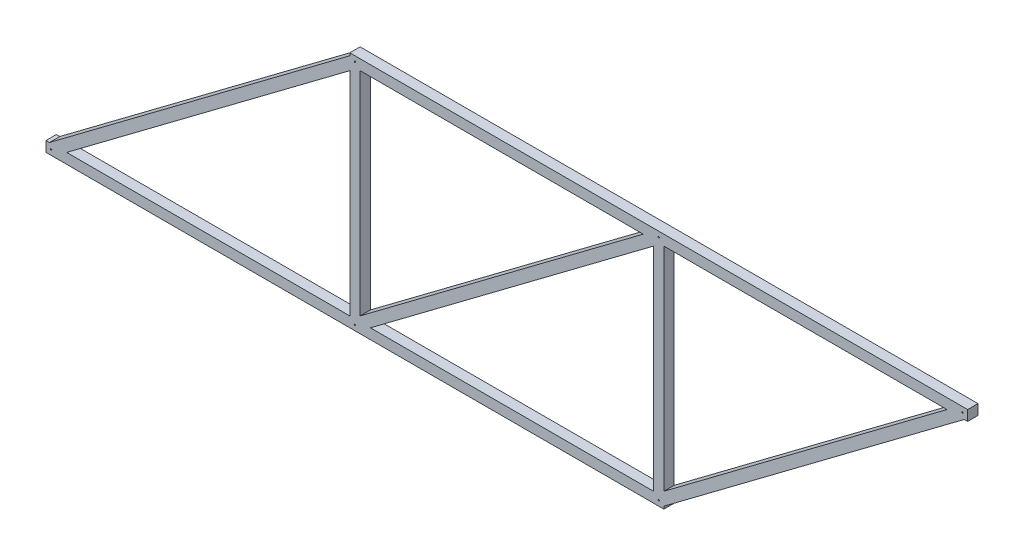
SolidWorks part; units mm, degrees
material "ASTM A36 Steel"
ref_plane "Front Plane" through (0, 0, 0) normal (0, 0, 1) x (1, 0, 0)
ref_plane "Top Plane" through (0, 0, 0) normal (0, 1, 0) x (1, 0, 0)
ref_plane "Right Plane" through (0, 0, 0) normal (1, 0, 0) x (0, 0, -1)
sketch "Sketch1" plane through (0, 0, 0) normal (0, 0, 1) x (1, 0, 0)
  line L0 (0, 321.0136) -> (0, -315.4549) construction
  line L1 (400, 0) -> (-400, 0)
  line L5 (0, 321.0136) -> (0, 1472.7719) construction
  line L6 (-572.3957, 13.6) -> (-402.2667, 13.6) construction
  line L8 (-6.8, 13.6) -> (-6.8, 293.2)
  line L10 (6.8, 300) -> (6.8, 20.4)
  line L11 (400, 33.5468) -> (400, -53.5726) construction
  line L12 (400, -53.5726) -> (400, 411.1646) construction
  line L16 (393.2, 33.5468) -> (406.8, 33.5468) construction
  line L17 (393.2, 25.8383) -> (393.2, 293.2) construction
  line L23 (-6.8, 49.2791) -> (6.8, 49.2791) construction
  line L24 (6.7962, 300) -> (6.7962, 313.6) construction
  line L26 (393.2, 13.6) -> (393.2, 293.2)
  line L27 (400, 0) -> (406.8, 0)
  line L28 (406.8, 0) -> (406.8, 3.4)
  line L30 (6.7962, 306.8) -> (6.8, 306.8) construction
  line L31 (-261.3797, 306.8) -> (-6.8, 306.8) construction
  line L33 (-400, 0) -> (-406.8, 0)
  line L34 (-402.2667, 13.6) -> (-406.8, 13.6)
  line L35 (-406.8, 13.6) -> (-406.8, 0)
  line L36 (-400, -3.859) -> (-400, 42.8765) construction
  line L38 (-7.1611, 306.8) -> (7.3756, 306.8) construction
  line L39 (-6.8, 306.8) -> (-261.3797, 306.8) construction
  line L40 (6.8, 306.8) -> (1587.7745, 306.8) construction
  line L41 (-400, 6.8) -> (-340.1161, 51.713) construction
  line L42 (-340.1161, 51.713) -> (248.532, 493.199) construction
  line L43 (-388.6667, 6.8) -> (-414.5578, 6.8) construction
  line L44 (-298.2024, 74.6482) -> (-421.7546, -18.016) construction
  line L45 (-298.2024, 74.6482) -> (178.5087, 432.1815) construction
  line L46 (-306.3624, 85.5282) -> (-440.6408, -15.1806) construction
  line L47 (-379.6, 13.6) -> (0, 13.6) construction
  line L48 (-440.6408, -15.1806) -> (172.2534, 444.49) construction
  line L49 (-298.2024, 74.6482) -> (-379.6, 13.6)
  line L50 (-298.2024, 74.6482) -> (-6.8, 293.2)
  line L51 (-306.3624, 85.5282) -> (-402.2667, 13.6)
  line L52 (-306.3624, 85.5282) -> (-6.8, 310.2)
  line L53 (-379.6, 13.6) -> (-6.8, 13.6)
  line L55 (-388.6667, 6.8) -> (-384.416, 6.8) construction
  line L56 (-414.5578, 6.8) -> (564.6934, 6.8) construction
  line L57 (0, 6.8) -> (400, 306.8) construction
  line L58 (400, 306.8) -> (487.4011, 372.3508) construction
  line L59 (20.4, 13.6) -> (393.2, 13.6)
  line L60 (106.2804, 95.0103) -> (-49.1953, -21.5965) construction
  line L61 (114.4404, 84.1303) -> (456.5641, 340.7231) construction
  line L62 (456.5641, 340.7231) -> (-49.1953, -38.5965) construction
  line L63 (-49.1953, -21.5965) -> (491.4944, 383.9208) construction
  line L64 (114.4404, 84.1303) -> (20.4, 13.6)
  line L65 (106.2804, 95.0103) -> (6.8, 20.4)
  line L66 (114.4404, 84.1303) -> (393.2, 293.2)
  line L67 (106.2804, 95.0103) -> (379.6, 300)
  line L68 (20.4, 13.6) -> (1791.4342, 13.6) construction
  line L69 (379.6, 300) -> (6.8, 300)
  line L74 (-6.8, 306.8) -> (-6.8, 332.6646) construction
  line L76 (800, 313.6) -> (800, 252.3532) construction
  line L77 (0, 313.6) -> (-6.8, 313.6)
  line L78 (6.8, 300) -> (6.7962, 300)
  line L79 (806.8, 310.2) -> (806.8, 333.5222) construction
  line L80 (806.8, 333.5222) -> (806.8, 282.6946) construction
  line L81 (-6.8, 310.2) -> (-6.8, 289.4988) construction
  line L82 (0, 313.6) -> (800, 313.6)
  line L83 (793.2, 310.2) -> (793.2, 335.5292) construction
  line L84 (793.2, 335.5292) -> (793.2, 283.6168) construction
  line L85 (802.2667, 300) -> (806.8, 300)
  line L86 (806.8, 300) -> (806.8, 310.2)
  line L87 (806.8, 313.6) -> (800, 313.6)
  line L88 (806.8, 313.6) -> (806.8, 309.6878)
  line L89 (-6.8, 313.6) -> (-6.8, 310.2)
  line L90 (400, 6.8) -> (444.2389, 39.9792) construction
  line L92 (429.5225, 37.4419) -> (406.8, 20.4) construction
  line L94 (437.6825, 26.5619) -> (406.8, 3.4) construction
  line L95 (386.7835, -11.6124) -> (391.571, -8.0217) construction
  line L96 (444.2389, 39.9792) -> (980.8855, 442.4641) construction
  line L97 (406.8, 20.4) -> (406.8, 300)
  line L98 (802.2667, 300) -> (406.8, 3.4)
  line L99 (406.8, 20.4) -> (779.6, 300) construction
  line L101 (406.8, 20.4) -> (779.6, 300)
  line L103 (391.571, -8.0217) -> (386.7835, -11.6124) construction
  line L104 (406.8, 3.4) -> (802.2667, 300) construction
  line L105 (779.6, 300) -> (406.8, 300)
  line L106 (816.8112, 327.9084) -> (891.4944, 383.9208) construction
  point P6 (0, 0)
  point P16 (0, 6.8)
  point P32 (400, 33.5468)
  point P40 (-396.6, 6.8)
  point P48 (0, 318.5638)
  point P55 (-400, 6.8)
  point P61 (-302.2824, 80.0882)
  point P70 (110.3604, 89.5703)
  point P86 (-6.8, 311.1511)
  point P96 (433.6025, 32.0019)
  point P98 (444.2389, 39.9792)
  dimension "D1" = 800
  dimension "D2" = 300
  dimension "D3" = 13.6
  dimension "D4" = 13.6
  dimension "D5" = 13.6
  dimension "D6" = 13.6
  dimension "D7" = 6.8
  dimension "D8" = 6.8
  dimension "D9" = 13.6
  dimension "D10" = 800
  dimension "D11" = 13.6
  dimension "D12" = 36.87
  dimension "D13" = 36.87
  dimension "D14" = 13.6
  dimension "D15" = 36.87
  dimension "D16" = 13.6
sketch "Sketch2" plane through (0, 0, 0) normal (0, 0, 1) x (1, 0, 0)
  line L0 (0, 321.0136) -> (0, 313.6) construction
  line L1 (400, 0) -> (-400, 0)
  line L5 (0, 321.0136) -> (0, 1472.7719) construction
  line L6 (-572.3957, 13.6) -> (-402.2667, 13.6) construction
  line L8 (-6.8, 13.6) -> (-6.8, 293.2)
  line L10 (6.8, 300) -> (6.8, 20.4)
  line L11 (400, 33.5468) -> (400, -53.5726) construction
  line L12 (400, -53.5726) -> (400, 411.1646) construction
  line L16 (393.2, 33.5468) -> (406.8, 33.5468) construction
  line L17 (393.2, 25.8383) -> (393.2, 293.2) construction
  line L23 (-6.8, 49.2791) -> (6.8, 49.2791) construction
  line L24 (-7.1611, 306.8) -> (7.3756, 306.8) construction
  line L26 (393.2, 13.6) -> (393.2, 293.2)
  line L27 (400, 0) -> (406.8, 0)
  line L28 (406.8, 0) -> (406.8, 3.4)
  line L30 (6.7893, 306.8) -> (6.8, 306.8) construction
  line L33 (-400, 0) -> (-406.8, 0)
  line L34 (-402.2667, 13.6) -> (-406.8, 13.6)
  line L35 (-406.8, 13.6) -> (-406.8, 0)
  line L36 (-400, -3.859) -> (-400, 42.8765) construction
  line L39 (-6.8, 306.8) -> (-261.3797, 306.8) construction
  line L40 (388.6667, 306.8) -> (1587.7745, 306.8) construction
  line L41 (-400, 6.8) -> (-340.1161, 51.713) construction
  line L43 (-388.6667, 6.8) -> (-414.5578, 6.8) construction
  line L44 (-298.2024, 74.6482) -> (-421.7546, -18.016) construction
  line L46 (-306.3624, 85.5282) -> (-440.6408, -15.1806) construction
  line L47 (-379.6, 13.6) -> (0, 13.6) construction
  line L48 (-440.6408, -15.1806) -> (0, 315.3) construction
  line L49 (-298.2024, 74.6482) -> (-379.6, 13.6)
  line L50 (-298.2024, 74.6482) -> (-6.8, 293.2)
  line L51 (-306.3624, 85.5282) -> (-402.2667, 13.6)
  line L52 (-306.3624, 85.5282) -> (-6.8, 310.2)
  line L53 (-379.6, 13.6) -> (-6.8, 13.6)
  line L55 (-388.6667, 6.8) -> (-384.416, 6.8) construction
  line L56 (-414.5578, 6.8) -> (564.6934, 6.8) construction
  line L57 (0, 6.8) -> (400, 306.8) construction
  line L58 (400, 306.8) -> (487.4011, 372.3508) construction
  line L59 (20.4, 13.6) -> (393.2, 13.6)
  line L60 (106.2804, 95.0103) -> (-49.1953, -21.5965) construction
  line L61 (114.4404, 84.1303) -> (456.5641, 340.7231) construction
  line L62 (456.5641, 340.7231) -> (-49.1953, -38.5965) construction
  line L63 (-49.1953, -21.5965) -> (491.4944, 383.9208) construction
  line L64 (114.4404, 84.1303) -> (20.4, 13.6)
  line L65 (106.2804, 95.0103) -> (6.8, 20.4)
  line L66 (114.4404, 84.1303) -> (393.2, 293.2)
  line L67 (106.2804, 95.0103) -> (379.6, 300)
  line L68 (20.4, 13.6) -> (1791.4342, 13.6) construction
  line L69 (379.6, 300) -> (6.8, 300)
  line L76 (800, 313.6) -> (800, 252.3532) construction
  line L77 (0, 313.6) -> (-6.8, 313.6)
  line L78 (6.8, 300) -> (6.7962, 300)
  line L79 (806.8, 310.2) -> (806.8, 333.5222) construction
  line L80 (806.8, 333.5222) -> (806.8, 282.6946) construction
  line L82 (0, 313.6) -> (800, 313.6)
  line L83 (793.2, 310.2) -> (793.2, 335.5292) construction
  line L84 (793.2, 335.5292) -> (793.2, 283.6168) construction
  line L85 (802.2667, 300) -> (806.8, 300)
  line L86 (806.8, 300) -> (806.8, 313.6)
  line L87 (806.8, 313.6) -> (800, 313.6)
  line L89 (-6.8, 313.6) -> (-6.8, 310.2)
  line L90 (400, 6.8) -> (444.2389, 39.9792) construction
  line L91 (6.7962, 306.8) -> (6.8, 306.8) construction
  line L92 (429.5225, 37.4419) -> (406.8, 20.4) construction
  line L94 (437.6825, 26.5619) -> (406.8, 3.4) construction
  line L95 (386.7835, -11.6124) -> (391.571, -8.0217) construction
  line L96 (444.2389, 39.9792) -> (980.8855, 442.4641) construction
  line L97 (406.8, 20.4) -> (406.8, 300)
  line L98 (802.2667, 300) -> (406.8, 3.4)
  line L99 (406.8, 20.4) -> (779.6, 300) construction
  line L101 (406.8, 20.4) -> (779.6, 300)
  line L103 (391.571, -8.0217) -> (386.7835, -11.6124) construction
  line L104 (406.8, 3.4) -> (802.2667, 300) construction
  line L105 (779.6, 300) -> (406.8, 300)
  line L106 (816.8112, 327.9084) -> (891.4944, 383.9208) construction
  circle A0 centre (0.1073, 306.8) radius 0.85
  circle A1 centre (-400, 6.8) radius 0.85
  circle A2 centre (0, 6.8) radius 0.85
  circle A3 centre (400, 6.8) radius 0.85
  circle A4 centre (800, 306.8) radius 0.85
  circle A5 centre (400, 306.8) radius 0.85
  point P6 (0, 0)
  point P16 (0, 6.8)
  point P32 (400, 33.5468)
  point P40 (-396.6, 6.8)
  point P48 (0, 318.5638)
  point P55 (-400, 6.8)
  point P61 (-302.2824, 80.0882)
  point P70 (110.3604, 89.5703)
  point P86 (-6.8, 311.1511)
  point P96 (433.6025, 32.0019)
  point P98 (444.2389, 39.9792)
  dimension "D17" = 1.7
  dimension "D18" = 1.7
  dimension "D19" = 1.7
  dimension "D20" = 1.7
  dimension "D21" = 1.7
  dimension "D22" = 1.7
  dimension "D1" = 800
  dimension "D2" = 300
  dimension "D3" = 13.6
  dimension "D4" = 13.6
  dimension "D5" = 13.6
  dimension "D6" = 13.6
  dimension "D7" = 6.8
  dimension "D8" = 6.8
  dimension "D9" = 13.6
  dimension "D10" = 800
  dimension "D11" = 13.6
  dimension "D12" = 36.87
  dimension "D13" = 36.87
  dimension "D14" = 13.6
  dimension "D15" = 36.87
  dimension "D16" = 13.6
extrude "Boss-Extrude1" add sketch "Sketch2" along normal blind 13.6 from surface at 0
